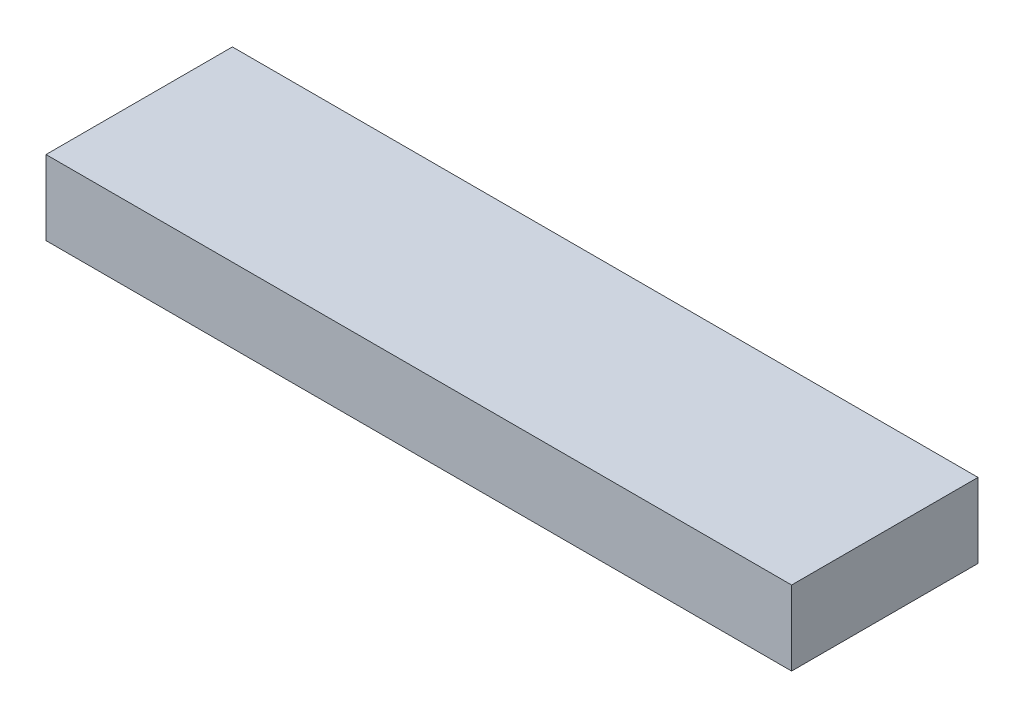
SolidWorks part; units mm, degrees
ref_plane "Front Plane" through (0, 0, 0) normal (0, 0, 1) x (1, 0, 0)
ref_plane "Top Plane" through (0, 0, 0) normal (0, 1, 0) x (1, 0, 0)
ref_plane "Right Plane" through (0, 0, 0) normal (1, 0, 0) x (0, 0, -1)
sketch "Sketch1" plane through (0, 0, 0) normal (0, 1, 0) x (1, 0, 0)
  line L1 (0, 0) -> (32, 0)
  line L2 (0, 0) -> (0, 8)
  line L3 (0, 8) -> (32, 8)
  line L4 (32, 0) -> (32, 8)
  dimension "D1" = 32
  dimension "D2" = 8
extrude "Boss-Extrude1" add sketch "Sketch1" along normal blind 3.2
shell "Shell1" thickness 1.6
